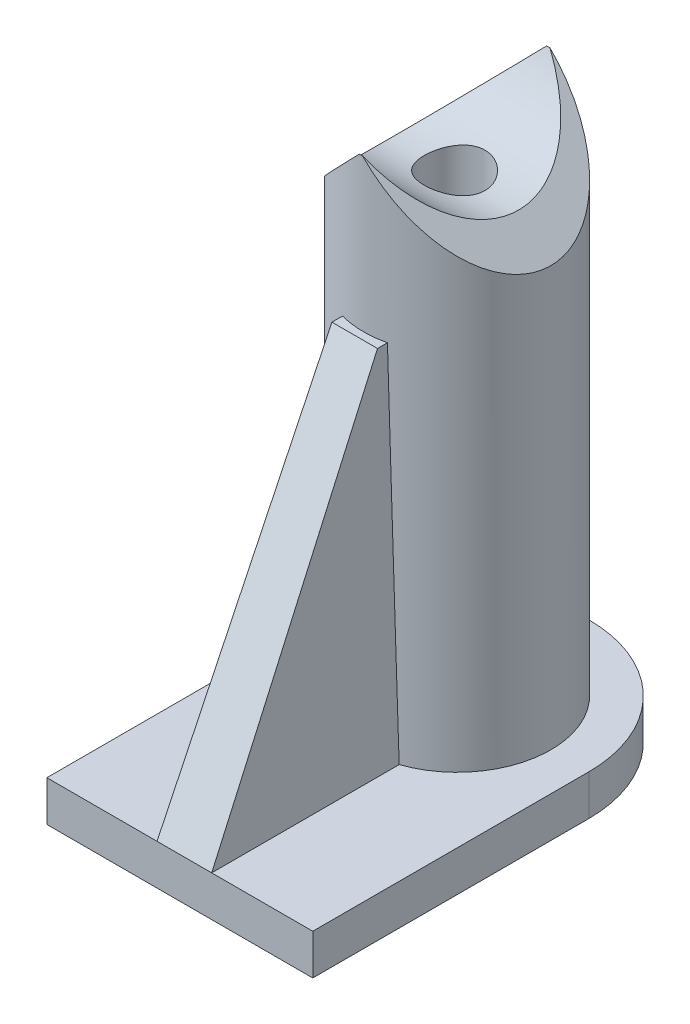
SolidWorks part; units mm, degrees
ref_plane "Front Plane" through (0, 0, 0) normal (0, 0, 1) x (1, 0, 0)
ref_plane "Top Plane" through (0, 0, 0) normal (0, 1, 0) x (1, 0, 0)
ref_plane "Right Plane" through (0, 0, 0) normal (1, 0, 0) x (0, 0, -1)
sketch "Sketch1" plane through (0, 0, 0) normal (0, 1, 0) x (1, 0, 0)
  line L1 (0, 0) -> (10.5, 0)
  line L2 (0, 0) -> (0, -16.1)
  line L3 (0, -16.1) -> (10.5, -16.1)
  line L4 (10.5, 0) -> (10.5, -16.1)
  dimension "D1" = 16.1
  dimension "D2" = 10.5
extrude "Boss-Extrude1" add sketch "Sketch1" along normal blind 1.6
fillet "Fillet1" radius 5.2 2 edges at (0, 0.8, 0) (10.5, 0.8, 0)
sketch "Sketch2" plane through (0, 1.6, 0) normal (0, 1, 0) x (1, 0, 0)
  circle A0 centre (5.2, -5.2) radius 3.7
  dimension "D1" = 7.4
extrude "Boss-Extrude2" add sketch "Sketch2" along normal blind 20.3
sketch "Sketch3" plane through (10.5, 0, 0) normal (1, 0, 0) x (0, 0, -1)
  circle A0 centre (-5.2, 23.4323) radius 4.0047
extrude "Cut-Extrude1" cut sketch "Sketch3" against normal blind 20.3
sketch "Sketch4" plane through (0, 1.6, 0) normal (0, 1, 0) x (1, 0, 0)
  line L0 (7.7906, -2.5583) -> (7.7906, -7.8417)
  arc A0 (7.7906, -7.8417) -> (7.7906, -2.5583) centre (5.2, -5.2) ccw
extrude "Cut-Extrude2" cut sketch "Sketch4" along normal through all from offset 14.8
sketch "Sketch5" plane through (0, 0, 16.1) normal (0, 0, 1) x (1, 0, 0)
  line L0 (5.3, 2.7251) -> (5.3, 23.2315) construction
  line L1 (6.8134, 19.4) -> (14.0852, 19.4) construction
  line L2 (8.9, 16.4) -> (7.7906, 16.4) construction
  line L3 (5.3, 21.959) -> (7.7906, 19.4)
  line L4 (7.7906, 20.4225) -> (7.7906, 16.4) construction
  line L5 (7.7906, 19.4) -> (9.8283, 21.3832)
  line L6 (9.8283, 21.3832) -> (4.5346, 26.8223)
  line L7 (5.3, 21.959) -> (1.5, 18.159)
  line L8 (1.5, 19.4276) -> (1.5, 1.6) construction
  line L9 (-0.1863, 21.959) -> (4.5346, 26.8223)
  line L10 (1.5, 18.159) -> (-0.1863, 21.959)
  dimension "D1" = 3
extrude "Cut-Extrude4" cut sketch "Sketch5" against normal blind 20.3
sketch "Sketch6" plane through (0, 0, 0) normal (0, -1, 0) x (-1, 0, 0)
  circle A0 centre (-5.3, -5.2) radius 2.275
  dimension "D1" = 4.55
extrude "Cut-Extrude5" cut sketch "Sketch6" against normal blind 16.3
chamfer "Chamfer1" distance 1 angle 45 1 edges at (5.3, 0, 2.925)
sketch "Sketch7" plane through (0, 16.3, 0) normal (0, -1, 0) x (1, 0, 0)
  circle A0 centre (5.3, 5.2) radius 1.2
  dimension "D1" = 2.4
extrude "Cut-Extrude6" cut sketch "Sketch7" against normal up to next
sketch "Sketch8" plane through (0, 0, 16.1) normal (0, 0, 1) x (1, 0, 0)
  line L0 (0, 1.6) -> (10.5, 1.6) construction
  line L1 (4.35, 15.9) -> (3.9912, 1.6)
  line L2 (3.9912, 1.6) -> (6.15, 1.6)
  line L3 (6.15, 15.9) -> (4.35, 15.9)
  line L4 (6.15, 1.6) -> (6.15, 15.9)
  point P0 (5.25, 1.6)
  dimension "D1" = 1.8
  dimension "D2" = 14.3
extrude "Boss-Extrude4" add sketch "Sketch8" against normal up to body separate body
sketch "Sketch11" plane through (6.15, 0, 0) normal (1, 0, 0) x (0, 0, -1)
  line L0 (-16.1, 1.6) -> (-9.1935, 15.9)
  line L1 (-8.776, 15.9) -> (-16.1, 15.9) construction
  line L2 (-9.1935, 15.9) -> (-16.1, 15.9)
  line L3 (-16.1, 15.9) -> (-16.1, 1.6)
  line L4 (-16.1, 1.6) -> (-16.0643, 1.5418)
  line M3 (-8.776, 15.9) -> (-16.1, 15.9)
  line M4 (-16.1, 15.9) -> (-16.1, 1.6)
extrude "Cut-Extrude8" cut sketch "Sketch11" against normal up to next contours L0 M4 M3
mirror "Mirror3" about plane through (0, 1.6, 0) normal (1, 0, 0) of bodies 112
delete or keep bodies "Body-Delete1" type delete bodies bodies 112
